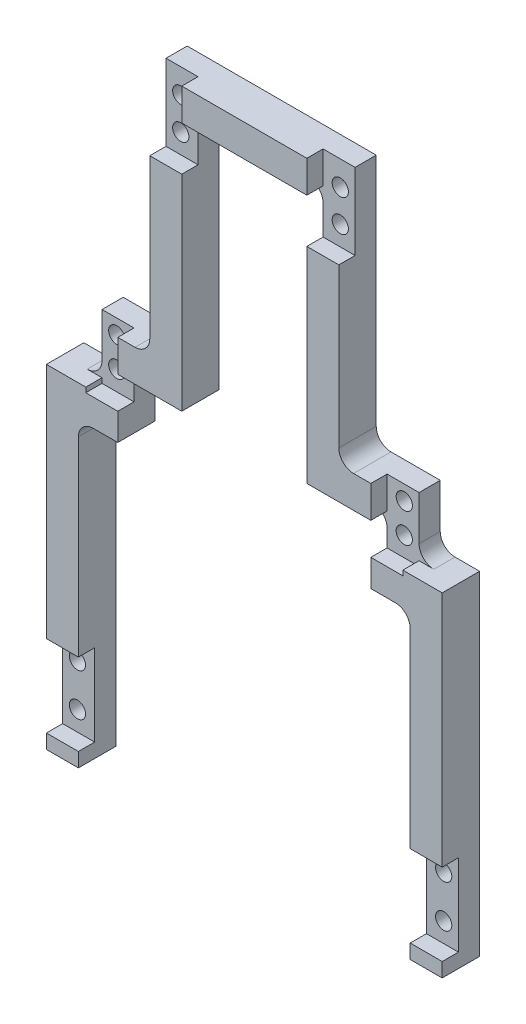
SolidWorks part; units mm, degrees
ref_plane "Front Plane" through (0, 0, 0) normal (0, 0, 1) x (1, 0, 0)
ref_plane "Top Plane" through (0, 0, 0) normal (0, 1, 0) x (1, 0, 0)
ref_plane "Right Plane" through (0, 0, 0) normal (1, 0, 0) x (0, 0, -1)
sketch "Sketch1" plane through (0, 0, 0) normal (0, 0, 1) x (1, 0, 0)
  line L0 (19.2, 59.55) -> (19.2, 8.85)
  line L1 (4, 8.85) -> (32.2, 8.85) construction
  line L2 (19.2, 8.85) -> (32.2, 8.85)
  line L3 (32.2, 8.85) -> (32.2, -3.15)
  line L4 (32.2, -3.15) -> (40.2, -3.15)
  line L5 (40.2, -3.15) -> (40.2, -77.4)
  line L6 (40.2, -77.4) -> (-40.2, -77.4)
  line L7 (0, 0) -> (0, 91.2085) construction
  line L8 (19.2, 59.55) -> (-19.2, 59.55)
  line L11 (-40.2, -3.15) -> (-40.2, -77.4)
  line L12 (-32.2, -3.15) -> (-40.2, -3.15)
  line L13 (-32.2, 8.85) -> (-32.2, -3.15)
  line L14 (-19.2, 8.85) -> (-32.2, 8.85)
  line L15 (-19.2, 59.55) -> (-19.2, 8.85)
  circle A0 centre (29.2, 5.85) radius 1.65
  circle A1 centre (29.2, -0.15) radius 1.65
  circle A2 centre (37.2, -55.4) radius 1.65
  circle A3 centre (37.2, -64) radius 1.65
  circle A4 centre (16.2, 48.05) radius 1.65
  circle A5 centre (16.2, 54.55) radius 1.65
  circle A6 centre (-16.2, 54.55) radius 1.65
  circle A7 centre (-16.2, 48.05) radius 1.65
  circle A8 centre (-37.2, -64) radius 1.65
  circle A9 centre (-37.2, -55.4) radius 1.65
  circle A10 centre (-29.2, -0.15) radius 1.65
  circle A11 centre (-29.2, 5.85) radius 1.65
  point P49 (0, 59.55)
  point P50 (0, -77.4)
  dimension "D1" = 3.3
extrude "Boss-Extrude1" add sketch "Sketch1" against normal up to surface (7.6 mm away)
sketch "Sketch2" plane through (0, 0, -7.6) normal (0, 0, -1) x (-1, 0, 0)
  line L0 (-19.2, 8.85) -> (-19.2, 59.55) construction
  line L1 (-19.2, 8.85) -> (-19.2, 59.55) construction
  line L2 (-19.2, 59.55) -> (19.2, 59.55) construction
  line L3 (19.2, 59.55) -> (19.2, 8.85) construction
  line L4 (19.2, 8.85) -> (32.2, 8.85) construction
  line L5 (32.2, 8.85) -> (32.2, -3.15) construction
  line L6 (32.2, -3.15) -> (40.2, -3.15) construction
  line L7 (40.2, -3.15) -> (40.2, -77.4) construction
  line L8 (40.2, -77.4) -> (-40.2, -77.4) construction
  line L9 (-40.2, -77.4) -> (-40.2, -3.15) construction
  line L10 (-40.2, -3.15) -> (-32.2, -3.15) construction
  line L11 (-32.2, -3.15) -> (-32.2, 8.85) construction
  line L12 (-32.2, 8.85) -> (-19.2, 8.85) construction
  line L13 (-19.2, 59.55) -> (19.2, 59.55) construction
  line L14 (19.2, 59.55) -> (19.2, 8.85) construction
  line L15 (19.2, 8.85) -> (32.2, 8.85) construction
  line L16 (32.2, 8.85) -> (32.2, -3.15) construction
  line L17 (32.2, -3.15) -> (40.2, -3.15) construction
  line L18 (40.2, -3.15) -> (40.2, -77.4) construction
  line L19 (40.2, -77.4) -> (-40.2, -77.4) construction
  line L20 (-40.2, -77.4) -> (-40.2, -3.15) construction
  line L21 (-40.2, -3.15) -> (-32.2, -3.15) construction
  line L22 (-32.2, -3.15) -> (-32.2, 8.85) construction
  line L23 (-32.2, 8.85) -> (-19.2, 8.85) construction
  line L24 (-12.7, 2.35) -> (-12.7, 53.05)
  line L25 (-12.7, 53.05) -> (12.7, 53.05)
  line L26 (12.7, 53.05) -> (12.7, 2.35)
  line L27 (12.7, 2.35) -> (25.7, 2.35)
  line L28 (25.7, 2.35) -> (25.7, -9.65)
  line L29 (25.7, -9.65) -> (33.7, -9.65)
  line L30 (33.7, -9.65) -> (33.7, -70.9)
  line L32 (-33.7, -70.9) -> (-33.7, -9.65)
  line L33 (-33.7, -9.65) -> (-25.7, -9.65)
  line L34 (-25.7, -9.65) -> (-25.7, 2.35)
  line L35 (-25.7, 2.35) -> (-12.7, 2.35)
  line L36 (33.7, -70.9) -> (40.2, -70.9)
  line L37 (-40.2, -77.4) -> (40.2, -77.4)
  line L38 (-40.2, -77.4) -> (-40.2, -70.9)
  line L39 (-40.2, -70.9) -> (-33.7, -70.9)
  line L40 (40.2, -77.4) -> (40.2, -70.9)
  line L41 (33.7, -70.9) -> (-33.7, -70.9) construction
  dimension "D1" = 6.5
extrude "Cut-Extrude1" cut sketch "Sketch2" against normal up to next
sketch "Sketch3" plane through (0, 0, 0) normal (0, 0, -1) x (-1, 0, 0)
  line L0 (40.2, -3.15) -> (40.2, -70.9) construction
  line L1 (12.7, 59.55) -> (19.2, 59.55)
  line L2 (12.7, 59.55) -> (12.7, 44.05)
  line L3 (12.7, 44.05) -> (19.2, 44.05)
  line L4 (19.2, 59.55) -> (19.2, 44.05)
  line L5 (25.7, 9.85) -> (32.2, 9.85)
  line L6 (25.7, 9.85) -> (25.7, -4.15)
  line L7 (25.7, -4.15) -> (32.2, -4.15)
  line L8 (32.2, 9.85) -> (32.2, -4.15)
  line L9 (33.7, -51.4) -> (40.2, -51.4)
  line L10 (33.7, -51.4) -> (33.7, -68)
  line L11 (33.7, -68) -> (40.2, -68)
  line L12 (40.2, -51.4) -> (40.2, -68)
  line L13 (33.7, -70.9) -> (33.7, -9.65) construction
  line L14 (32.2, 8.85) -> (32.2, -3.15) construction
  line L15 (25.7, -9.65) -> (25.7, 2.35) construction
  line L16 (19.2, 59.55) -> (19.2, 8.85) construction
  line L17 (12.7, 2.35) -> (12.7, 53.05) construction
  circle A0 centre (16.2, 54.55) radius 1.65 construction
  circle A1 centre (16.2, 48.05) radius 1.65 construction
  circle A2 centre (29.2, 5.85) radius 1.65 construction
  circle A3 centre (29.2, -0.15) radius 1.65 construction
  circle A4 centre (37.2, -55.4) radius 1.65 construction
  circle A5 centre (37.2, -64) radius 1.65 construction
  dimension "D1" = 5
  dimension "D2" = 4
  dimension "D4" = 4
  dimension "D5" = 4
  dimension "D3" = 4
  dimension "D6" = 4
extrude "Cut-Extrude2" cut sketch "Sketch3" along normal blind 3.3
mirror "Mirror1" about plane through (0, 0, 0) normal (1, 0, 0) of "Cut-Extrude2"
fillet "Fillet1" radius 3 10 edges at (19.2, 8.85, -3.8) (32.2, -3.15, -5.45) (-19.2, 8.85, -3.8) (-32.2, -3.15, -5.45) (-33.7, -9.65, -3.8) (-25.7, 2.35, -5.45) (33.7, -9.65, -3.8) (25.7, 2.35, -5.45) (12.7, 53.05, -5.45) (-12.7, 53.05, -5.45)
